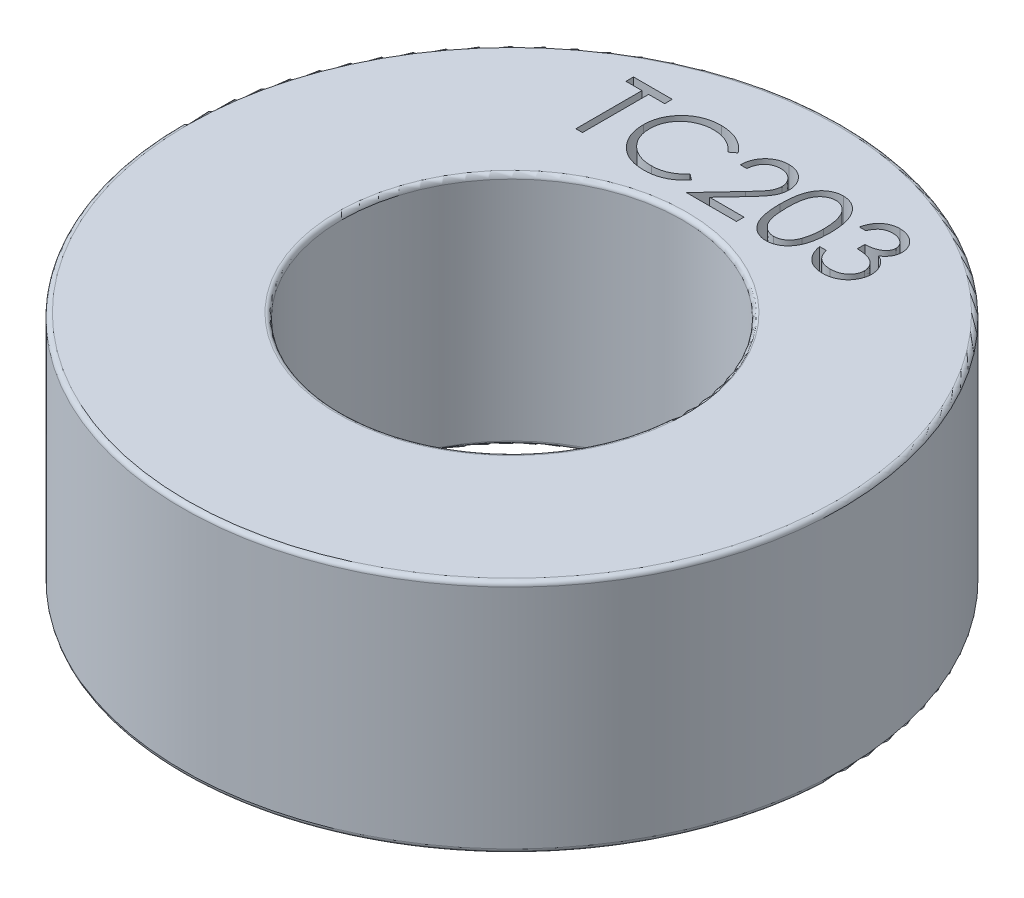
SolidWorks part; units mm, degrees
ref_plane "Front Plane" through (0, 0, 0) normal (0, 0, 1) x (1, 0, 0)
ref_plane "Top Plane" through (0, 0, 0) normal (0, 1, 0) x (1, 0, 0)
ref_plane "Right Plane" through (0, 0, 0) normal (1, 0, 0) x (0, 0, -1)
sketch "Toroidal Core TC229" plane through (0, 0, 0) normal (0, 0, 1) x (1, 0, 0)
  line L0 (0, -8.108) -> (0, 13.3131) construction
  line L2 (5.6461, 0) -> (10.5039, 0)
  line L3 (5.5, 0.1461) -> (5.5, 7.4739)
  line L4 (5.6461, 7.62) -> (10.5039, 7.62)
  line L5 (10.65, 0.1461) -> (10.65, 7.4739)
  arc A0 (5.6461, 0) -> (5.5, 0.1461) centre (5.6461, 0.1461) cw
  arc A1 (10.5039, 0) -> (10.65, 0.1461) centre (10.5039, 0.1461) ccw
  arc A2 (10.5039, 7.62) -> (10.65, 7.4739) centre (10.5039, 7.4739) cw
  arc A3 (5.5, 7.4739) -> (5.6461, 7.62) centre (5.6461, 7.4739) cw
  point P9 (5.5, 0)
  point P12 (10.65, 0)
  point P15 (10.65, 7.62)
  point P18 (5.5, 7.62)
  dimension "D4" = 0.1461
  dimension "D1" = 5.15
  dimension "D2" = 7.62
  dimension "D3" = 5.5
revolve "Revolve2" add sketch "Toroidal Core TC229" angle 360 about L0
sketch "Sketch1" plane through (0, 7.62, 0) normal (0, 1, 0) x (1, 0, 0)
  text T0 "TC203\r\n" font "Century Gothic" height in points 9
extrude "Cut-Extrude1" cut sketch "Sketch1" against normal blind 1
